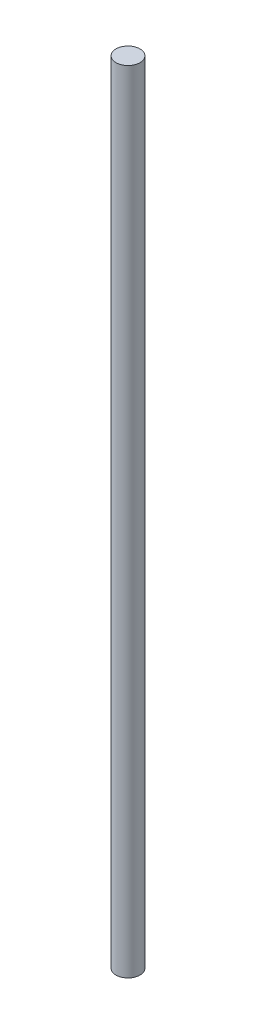
SolidWorks part; units mm, degrees
material "1060 Alloy"
ref_plane "Front Plane" through (0, 0, 0) normal (0, 0, 1) x (1, 0, 0)
ref_plane "Top Plane" through (0, 0, 0) normal (0, 1, 0) x (1, 0, 0)
ref_plane "Right Plane" through (0, 0, 0) normal (1, 0, 0) x (0, 0, -1)
sketch "Sketch1" plane through (0, 0, 0) normal (0, 1, 0) x (1, 0, 0)
  circle A0 centre (0, 0) radius 5
  dimension "D1" = 10
extrude "Boss-Extrude1" add sketch "Sketch1" along normal blind 330.2
